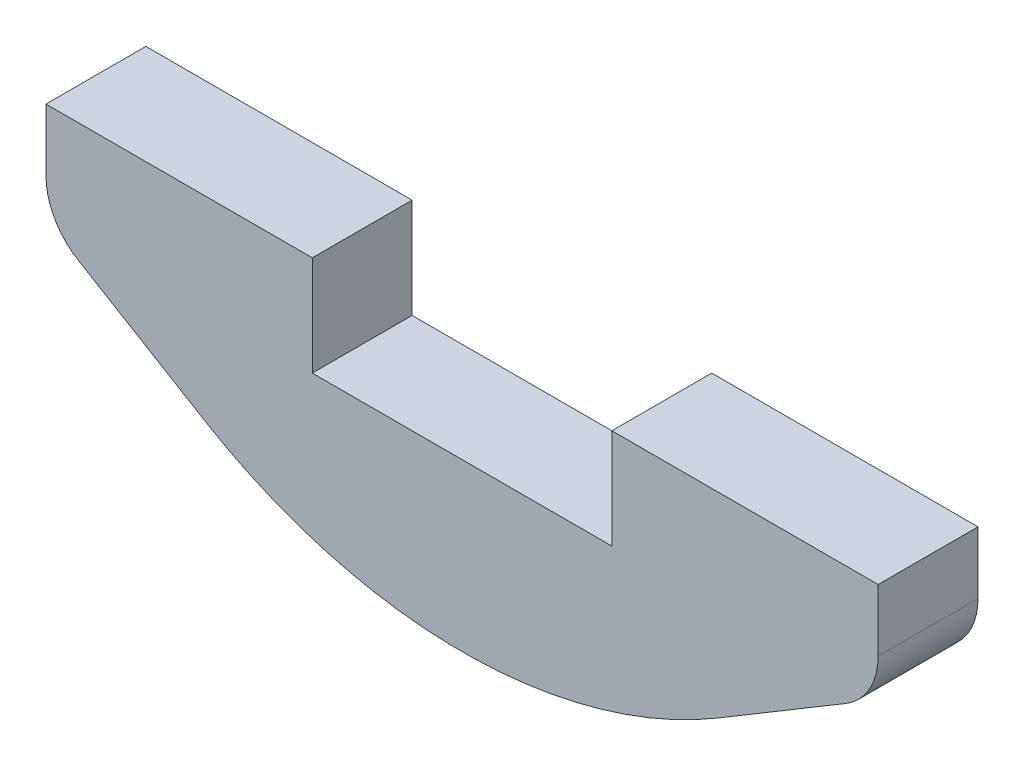
SolidWorks part; units mm, degrees
ref_plane "Alzado" through (0, 0, 0) normal (0, 0, 1) x (1, 0, 0)
ref_plane "Planta" through (0, 0, 0) normal (0, 1, 0) x (1, 0, 0)
ref_plane "Vista lateral" through (0, 0, 0) normal (1, 0, 0) x (0, 0, -1)
sketch "Croquis1" plane through (0, 0, 0) normal (0, 0, 1) x (1, 0, 0)
  line L0 (-12.5, 0) -> (12.5, 0)
  line L1 (0, 0) -> (0, 10) construction
  line L2 (0, 0) -> (0, -5) construction
  line L3 (-12.5, 0) -> (-7.7033, -2.8709)
  line L4 (12.5, 0) -> (7.7033, -2.8709)
  line L6 (-12.5, 0) -> (-4.5, 0)
  line L7 (-12.5, 0) -> (-12.5, 3)
  line L8 (-12.5, 3) -> (-4.5, 3)
  line L9 (-4.5, 0) -> (-4.5, 3)
  line L10 (12.5, 0) -> (4.5, 0)
  line L11 (12.5, 0) -> (12.5, 3)
  line L12 (12.5, 3) -> (4.5, 3)
  line L13 (4.5, 0) -> (4.5, 3)
  arc A0 (-7.7033, -2.8709) -> (7.7033, -2.8709) centre (0, 10) ccw
  point P4 (0, 0)
  dimension "D3" = 15
  dimension "D1" = 25
  dimension "D2" = 5
  dimension "D4" = 3
  dimension "D5" = 8
  dimension "D6" = 8
extrude "Saliente-Extruir1" add sketch "Croquis1" along normal blind 3 contours L3 A0 L4 L0 | L0 L9 L8 L7 | L13 L0 L11 L12
fillet "Redondeo1" radius 2 2 edges at (12.5, 0, 1.5) (-12.5, 0, 1.5)
